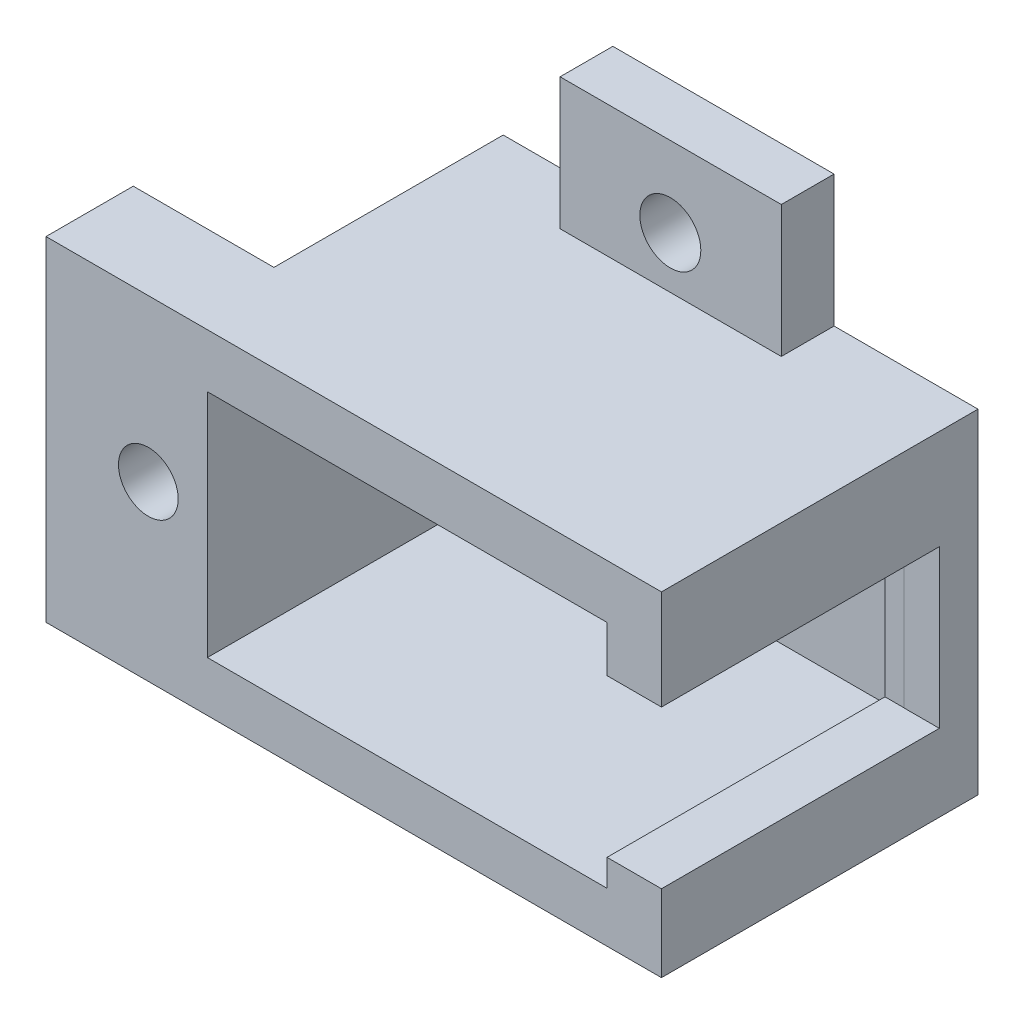
SolidWorks part; units mm, degrees
ref_plane "Front Plane" through (0, 0, 0) normal (0, 0, 1) x (1, 0, 0)
ref_plane "Top Plane" through (0, 0, 0) normal (0, 1, 0) x (1, 0, 0)
ref_plane "Right Plane" through (0, 0, 0) normal (1, 0, 0) x (0, 0, -1)
sketch "Sketch1" plane through (0, 0, 0) normal (0, 0, 1) x (1, 0, 0)
  line L1 (-1.0933, 0.8351) -> (1.4067, 0.8351)
  line L2 (-1.0933, 0.8351) -> (-1.0933, -0.6649)
  line L3 (-1.0933, -0.6649) -> (1.4067, -0.6649)
  line L4 (1.4067, 0.8351) -> (1.4067, -0.6649)
  dimension "D1" = 2.5
  dimension "D2" = 1.5
extrude "Boss-Extrude1" add sketch "Sketch1" along normal blind 1.8
sketch "Sketch2" plane through (0, 0, 1.8) normal (0, 0, 1) x (1, 0, 0)
  line L1 (-0.9755, 0.7298) -> (1.2972, 0.7298)
  line L2 (-0.9755, 0.7298) -> (-0.9755, -0.5795)
  line L3 (-0.9755, -0.5795) -> (1.2972, -0.5795)
  line L4 (1.2972, 0.7298) -> (1.2972, -0.5795)
extrude "Cut-Extrude1" cut sketch "Sketch2" against normal blind 1.7
sketch "Sketch3" plane through (1.4067, 0, 0) normal (1, 0, 0) x (0, 0, -1)
  line L1 (-0.2922, -0.4617) -> (-0.2902, -0.4617)
  line L2 (-0.2922, -0.4617) -> (-0.2922, -0.459)
  line L3 (-0.2922, -0.459) -> (-0.2902, -0.459)
  line L4 (-0.2902, -0.4617) -> (-0.2902, -0.459)
  line L5 (-0.2193, -0.427) -> (-1.6684, -0.427)
  line L6 (-0.2193, -0.427) -> (-0.2193, 0.4688)
  line L7 (-0.2193, 0.4688) -> (-1.6684, 0.4688)
  line L8 (-1.6684, -0.427) -> (-1.6684, 0.4688)
extrude "Cut-Extrude2" cut sketch "Sketch3" against normal blind 1.8
scale "Scale1" scale about centroid uniform scaling yes scale factor 10
sketch "Sketch6" plane through (13.765, 0, 0) normal (1, 0, 0) x (0, 0, -1)
  line L0 (-10.0899, -5.3785) -> (4.4011, -5.3785) construction
  line L1 (-12.7162, 3.5683) -> (-9.3169, 3.5683)
  line L2 (-12.7162, 3.5683) -> (-12.7162, -5.3785)
  line L3 (-12.7162, -5.3785) -> (-9.3169, -5.3785)
  line L4 (-9.3169, 3.5683) -> (-9.3169, -5.3785)
extrude "Cut-Extrude4" cut sketch "Sketch6" against normal blind 10
sketch "Sketch12" plane through (-11.235, 0, 0) normal (-1, 0, 0) x (0, 0, 1)
  line L1 (11.4058, 7.2418) -> (-6.5942, 7.2418) construction
  line L3 (6.4439, 7.2418) -> (11.4058, 7.2418)
  line L4 (6.4439, 7.2418) -> (6.4439, -7.7582)
  line L5 (6.4439, -7.7582) -> (11.4058, -7.7582)
  line L6 (11.4058, 7.2418) -> (11.4058, -7.7582)
extrude "Boss-Extrude5" add sketch "Sketch12" along normal blind 8
sketch "Sketch13" plane through (0, 0, 11.4058) normal (0, 0, 1) x (1, 0, 0)
  circle A0 centre (-13.4157, 0.0718) radius 1.6988
extrude "Cut-Extrude6" cut sketch "Sketch13" against normal blind 34 contours A0
sketch "Sketch22" plane through (0, 0, -6.5942) normal (0, 0, -1) x (-1, 0, 0)
  line L0 (-13.765, 7.2418) -> (11.235, 7.2418) construction
  line L1 (-7.5797, 7.2418) -> (5, 7.2418)
  line L2 (-7.5797, 7.2418) -> (-7.5797, 16.7274)
  line L3 (-7.5797, 16.7274) -> (5, 16.7274)
  line L4 (5, 7.2418) -> (5, 16.7274)
  line L5 (-13.765, -0.2582) -> (11.235, -0.2582) construction
  line L6 (-13.765, -7.7582) -> (-13.765, 7.2418) construction
  line L7 (11.235, 7.2418) -> (11.235, -7.7582) construction
  line L8 (-7.5797, -17.2437) -> (5, -17.2437)
  line L9 (5, -7.7582) -> (5, -17.2437)
  line L10 (-7.5797, -7.7582) -> (5, -7.7582)
  line L11 (-7.5797, -7.7582) -> (-7.5797, -17.2437)
extrude "Boss-Extrude10" add sketch "Sketch22" against normal blind 3
sketch "Sketch25" plane through (0, 0, -3.5942) normal (0, 0, 1) x (1, 0, 0)
  line L0 (-10.0573, -0.3569) -> (12.6698, -0.3569) construction
  line L1 (-10.0573, 6.1898) -> (-10.0573, -6.9036) construction
  line L2 (12.6698, -6.9036) -> (12.6698, 6.1898) construction
  circle A0 centre (1.2686, 12.1797) radius 1.7335
  circle A1 centre (1.2686, -12.8935) radius 1.7335
extrude "Cut-Extrude7" cut sketch "Sketch25" against normal blind 36
sketch "Sketch26" plane through (0, 7.2418, 0) normal (0, 1, 0) x (1, 0, 0)
  line L0 (13.765, -11.4058) -> (-19.235, -11.4058) construction
  line L1 (-11.235, 6.5942) -> (-4.9881, 6.5942)
  line L2 (-11.235, 6.5942) -> (-11.235, -11.4058)
  line L3 (-11.235, -11.4058) -> (-4.9881, -11.4058)
  line L4 (-4.9881, 6.5942) -> (-4.9881, -11.4058)
extrude "Boss-Extrude11" add sketch "Sketch26" along normal blind 2
sketch "Sketch27" plane through (0, 7.2418, 0) normal (0, 1, 0) x (1, 0, 0)
  line L0 (13.765, -11.4058) -> (-4.9881, -11.4058) construction
  line L1 (13.765, 6.5942) -> (6.7705, 6.5942)
  line L2 (13.765, 6.5942) -> (13.765, -11.4058)
  line L3 (13.765, -11.4058) -> (6.7705, -11.4058)
  line L4 (6.7705, 6.5942) -> (6.7705, -11.4058)
  point P7 (6.7705, -11.4058)
extrude "Boss-Extrude12" add sketch "Sketch27" along normal blind 2
sketch "Sketch28" plane through (0, 7.2418, 0) normal (0, 1, 0) x (1, 0, 0)
  line L1 (-5, 3.5942) -> (6.7705, 3.5942)
  line L2 (-5, 3.5942) -> (-5, -11.4058)
  line L3 (-5, -11.4058) -> (6.7705, -11.4058)
  line L4 (6.7705, 3.5942) -> (6.7705, -11.4058)
extrude "Boss-Extrude13" add sketch "Sketch28" along normal blind 2
sketch "Sketch29" plane through (0, -7.7582, 0) normal (0, -1, 0) x (-1, 0, 0)
  line L0 (19.235, -11.4058) -> (-13.765, -11.4058) construction
  line L1 (11.235, 6.5942) -> (3.6855, 6.5942)
  line L2 (11.235, 6.5942) -> (11.235, -11.4058)
  line L3 (11.235, -11.4058) -> (3.6855, -11.4058)
  line L4 (3.6855, 6.5942) -> (3.6855, -11.4058)
  point P7 (3.6855, -11.4058)
extrude "Boss-Extrude14" add sketch "Sketch29" along normal blind 2
sketch "Sketch30" plane through (0, -7.7582, 0) normal (0, -1, 0) x (-1, 0, 0)
  line L0 (3.6855, -11.4058) -> (-13.765, -11.4058) construction
  line L1 (-13.765, 6.5942) -> (-7.6155, 6.5942)
  line L2 (-13.765, 6.5942) -> (-13.765, -11.4058)
  line L3 (-13.765, -11.4058) -> (-7.6155, -11.4058)
  line L4 (-7.6155, 6.5942) -> (-7.6155, -11.4058)
extrude "Boss-Extrude15" add sketch "Sketch30" along normal blind 2
sketch "Sketch31" plane through (0, -7.7582, 0) normal (0, -1, 0) x (1, 0, 0)
  line L1 (-3.6855, 11.4058) -> (7.5797, 11.4058)
  line L2 (-3.6855, 11.4058) -> (-3.6855, -3.5942)
  line L3 (-3.6855, -3.5942) -> (7.5797, -3.5942)
  line L4 (7.5797, 11.4058) -> (7.5797, -3.5942)
extrude "Boss-Extrude16" add sketch "Sketch31" along normal blind 2
sketch "Sketch32" plane through (0, 7.2418, 0) normal (0, 1, 0) x (1, 0, 0)
  line L1 (-19.235, -6.4439) -> (-11.235, -6.4439)
  line L2 (-19.235, -6.4439) -> (-19.235, -11.4058)
  line L3 (-19.235, -11.4058) -> (-11.235, -11.4058)
  line L4 (-11.235, -6.4439) -> (-11.235, -11.4058)
extrude "Boss-Extrude17" add sketch "Sketch32" along normal blind 2
sketch "Sketch33" plane through (0, -7.7582, 0) normal (0, -1, 0) x (-1, 0, 0)
  line L1 (-7.5797, -11.4058) -> (-7.6155, -11.4058)
  line L2 (-7.5797, -11.4058) -> (-7.5797, 6.5942)
  line L3 (-7.5797, 6.5942) -> (-7.6155, 6.5942)
  line L4 (-7.6155, -11.4058) -> (-7.6155, 6.5942)
extrude "Boss-Extrude18" add sketch "Sketch33" along normal blind 2
sketch "Sketch34" plane through (0, -7.7582, 0) normal (0, -1, 0) x (1, 0, 0)
  line L1 (-19.235, 11.4058) -> (-11.235, 11.4058)
  line L2 (-19.235, 11.4058) -> (-19.235, 6.4439)
  line L3 (-19.235, 6.4439) -> (-11.235, 6.4439)
  line L4 (-11.235, 11.4058) -> (-11.235, 6.4439)
extrude "Boss-Extrude19" add sketch "Sketch34" along normal blind 2
sketch "Sketch36" plane through (13.765, 0, 0) normal (1, 0, 0) x (0, 0, -1)
  line L0 (6.5942, -9.7582) -> (6.5942, 9.2418) construction
  line L1 (-11.4058, -9.7582) -> (6.5942, -9.7582)
  line L2 (-11.4058, -9.7582) -> (-11.4058, -5.4407)
  line L3 (-11.4058, -5.4407) -> (6.5942, -5.4407)
  line L4 (6.5942, -9.7582) -> (6.5942, -5.4407)
extrude "Boss-Extrude20" add sketch "Sketch36" along normal blind 2
sketch "Sketch37" plane through (13.765, 0, 0) normal (1, 0, 0) x (0, 0, -1)
  line L0 (6.5942, -5.4407) -> (6.5942, 9.2418) construction
  line L1 (-11.4058, 9.2418) -> (6.5942, 9.2418)
  line L2 (-11.4058, 9.2418) -> (-11.4058, 3.6111)
  line L3 (-11.4058, 3.6111) -> (6.5942, 3.6111)
  line L4 (6.5942, 9.2418) -> (6.5942, 3.6111)
extrude "Boss-Extrude21" add sketch "Sketch37" along normal blind 2
sketch "Sketch38" plane through (13.765, 0, 0) normal (1, 0, 0) x (0, 0, -1)
  line L0 (6.5942, -5.4407) -> (-11.4058, -5.4407) construction
  line L1 (6.5942, 3.6111) -> (4.3948, 3.6111)
  line L2 (6.5942, 3.6111) -> (6.5942, -5.4407)
  line L3 (6.5942, -5.4407) -> (4.3948, -5.4407)
  line L4 (4.3948, 3.6111) -> (4.3948, -5.4407)
extrude "Boss-Extrude22" add sketch "Sketch38" along normal blind 2
sketch "Sketch39" plane through (13.765, 0, 0) normal (1, 0, 0) x (0, 0, -1)
  line L1 (-11.4058, 3.5683) -> (4.3948, 3.5683)
  line L2 (-11.4058, 3.5683) -> (-11.4058, 3.6111)
  line L3 (-11.4058, 3.6111) -> (4.3948, 3.6111)
  line L4 (4.3948, 3.5683) -> (4.3948, 3.6111)
extrude "Boss-Extrude23" add sketch "Sketch39" along normal blind 2
sketch "Sketch40" plane through (13.765, 0, 0) normal (1, 0, 0) x (0, 0, -1)
  line L1 (-11.4058, -5.4407) -> (4.3948, -5.4407)
  line L2 (-11.4058, -5.4407) -> (-11.4058, -5.3785)
  line L3 (-11.4058, -5.3785) -> (4.3948, -5.3785)
  line L4 (4.3948, -5.4407) -> (4.3948, -5.3785)
extrude "Boss-Extrude24" add sketch "Sketch40" along normal blind 2
